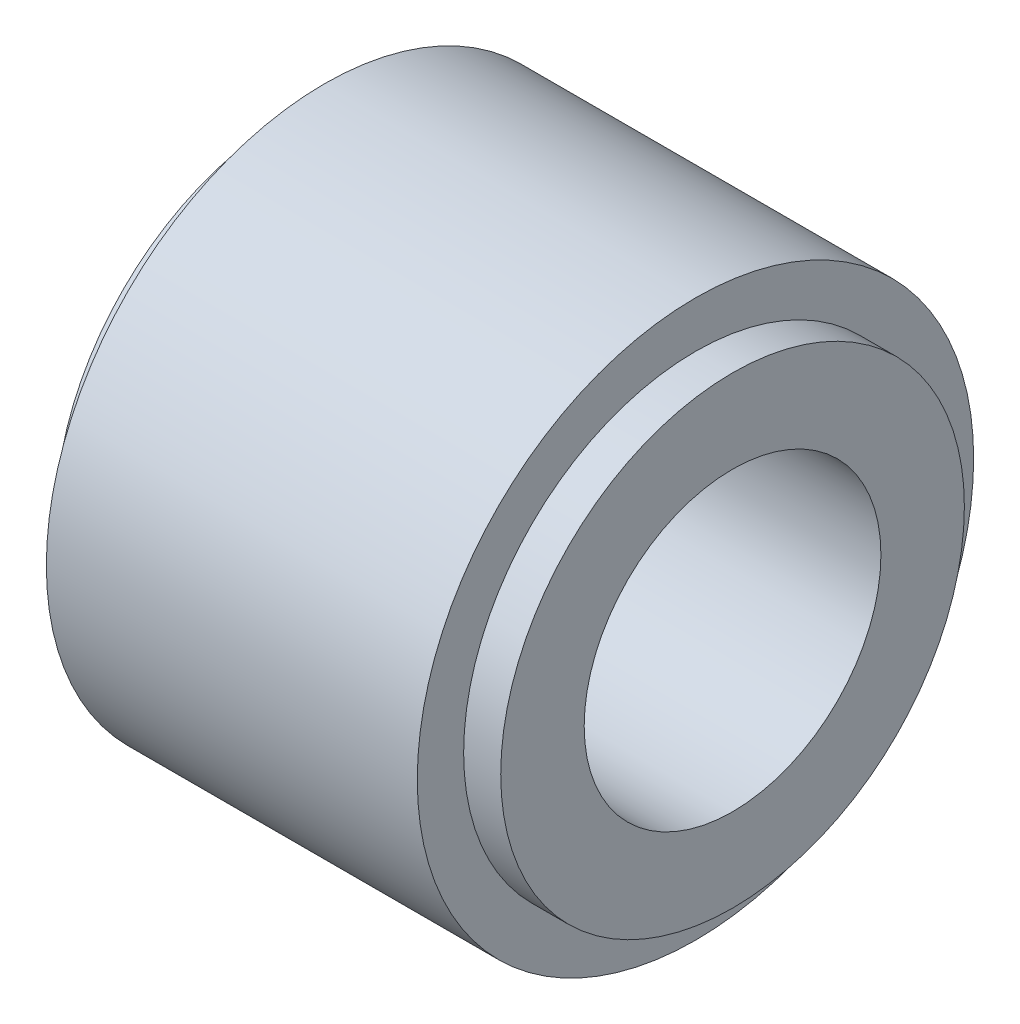
SolidWorks part; units mm, degrees
ref_plane "Front" through (0, 0, 0) normal (0, 0, 1) x (1, 0, 0)
ref_plane "Top" through (0, 0, 0) normal (0, 1, 0) x (1, 0, 0)
ref_plane "Right" through (0, 0, 0) normal (1, 0, 0) x (0, 0, -1)
sketch "Sketch1" plane through (0, 0, 0) normal (0, 0, 1) x (1, 0, 0)
  line L0 (-4.0472, 0) -> (28.2496, 0) construction
  line L1 (0, 0) -> (0, 12.5)
  line L2 (0, 12.5) -> (2, 12.5)
  line L3 (2, 12.5) -> (2, 15)
  line L4 (2, 15) -> (22, 15)
  line L5 (22, 15) -> (22, 12.5)
  line L6 (22, 12.5) -> (24, 12.5)
  line L7 (24, 12.5) -> (24, 0)
  line L8 (24, 0) -> (0, 0)
  dimension "D1" = 30
  dimension "D2" = 25
  dimension "D3" = 24
  dimension "D4" = 2
  dimension "D5" = 22
revolve "Revolve1" add sketch "Sketch1" angle 360 about L0
sketch "Sketch2" plane through (0, 0, 0) normal (0, 0, 1) x (1, 0, 0)
  line L0 (-2.9686, 0) -> (26.889, 0) construction
  line L1 (24, -12.5) -> (24, 12.5) construction
  line L2 (0, 0) -> (24, 0)
  line L3 (0, 0) -> (0, 8)
  line L4 (0, 8) -> (24, 8)
  line L5 (24, 0) -> (24, 8)
  dimension "D1" = 16
revolve "Cut-Revolve1" cut sketch "Sketch2" angle 360 about L0
